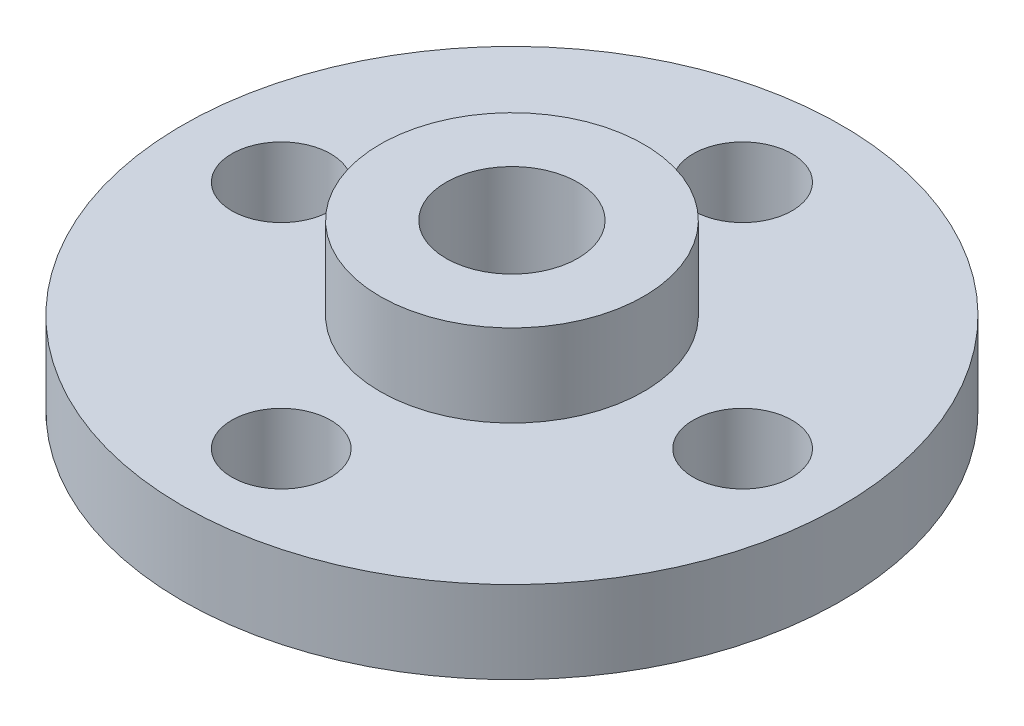
SolidWorks part; units mm, degrees
ref_plane "前视基准面" through (0, 0, 0) normal (0, 0, 1) x (1, 0, 0)
ref_plane "上视基准面" through (0, 0, 0) normal (0, 1, 0) x (1, 0, 0)
ref_plane "右视基准面" through (0, 0, 0) normal (1, 0, 0) x (0, 0, -1)
other "Configuration Table"
sketch "草图1" plane through (0, 0, 0) normal (0, 1, 0) x (1, 0, 0)
  circle A0 centre (0, 0) radius 10
  circle A1 centre (0, 0) radius 2
  dimension "D1" = 20
  dimension "D2" = 4
extrude "凸台-拉伸1" add sketch "草图1" along normal blind 2.5
sketch "草图2" plane through (0, 2.5, 0) normal (0, 1, 0) x (1, 0, 0)
  circle A0 centre (0, 0) radius 2
  circle A1 centre (0, 0) radius 4
  dimension "D1" = 8
  dimension "D2" = 4
extrude "凸台-拉伸2" add sketch "草图2" along normal blind 2.5
sketch "草图3" plane through (0, 2.5, 0) normal (0, 1, 0) x (1, 0, 0)
  circle A0 centre (0, 0) radius 7 construction
  circle A1 centre (0, 7) radius 1.5
  circle A2 centre (7, 0) radius 1.5
  circle A3 centre (0, -7) radius 1.5
  circle A4 centre (-7, 0) radius 1.5
  dimension "D1" = 14
  dimension "D2" = 3
extrude "切除-拉伸1" cut sketch "草图3" against normal blind 2.5
